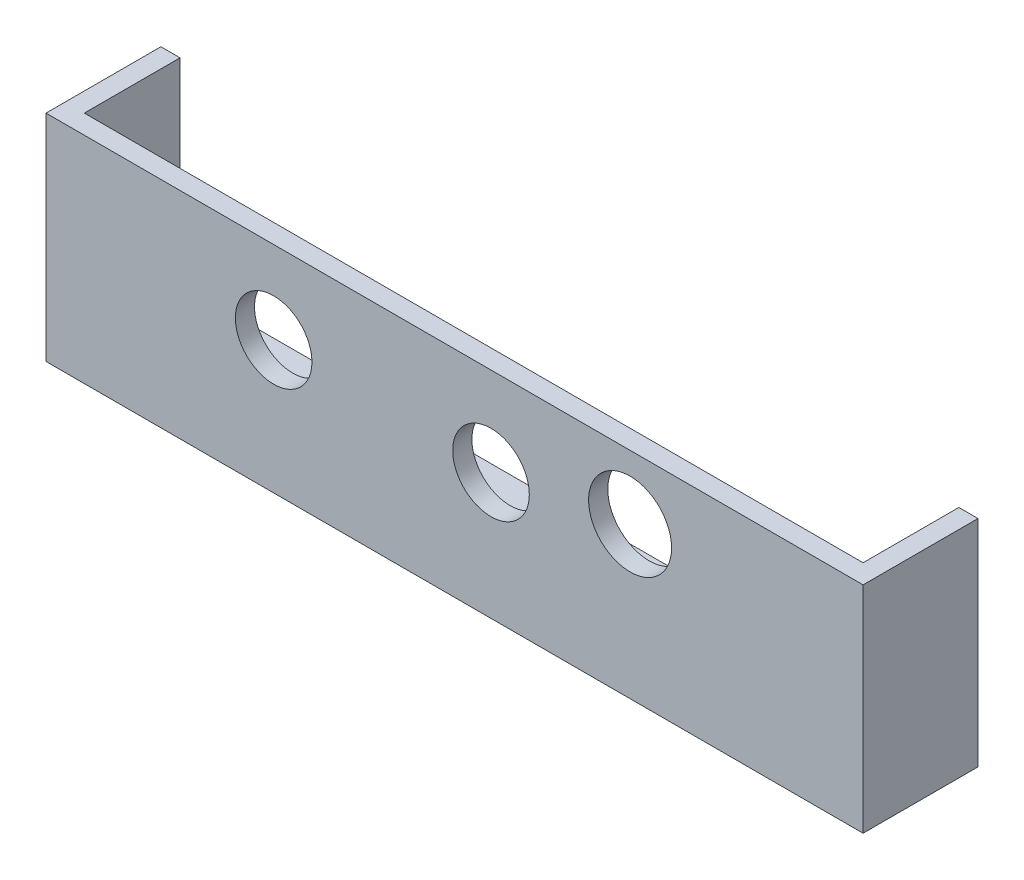
SolidWorks part; units mm, degrees
ref_plane "前基準面" through (0, 0, 0) normal (0, 0, 1) x (1, 0, 0)
ref_plane "上基準面" through (0, 0, 0) normal (0, 1, 0) x (1, 0, 0)
ref_plane "右基準面" through (0, 0, 0) normal (1, 0, 0) x (0, 0, -1)
sketch "草圖1" plane through (0, 0, 0) normal (0, 0, 1) x (1, 0, 0)
  line L1 (-94.9808, -38.4301) -> (33.0192, -38.4301)
  line L2 (-94.9808, -38.4301) -> (-94.9808, -72.1301)
  line L3 (-94.9808, -72.1301) -> (33.0192, -72.1301)
  line L4 (33.0192, -38.4301) -> (33.0192, -72.1301)
  line L5 (-84.9808, -38.4301) -> (23.0192, -38.4301) construction
  line L6 (-84.9808, -68.6301) -> (23.0192, -68.6301) construction
  line L7 (29.0192, -38.4301) -> (29.0192, -68.6301) construction
  line L8 (-90.9808, -38.4301) -> (-90.9808, -68.6301) construction
  circle A0 centre (-3.4808, -48.4301) radius 6.5
  circle A1 centre (-25.2697, -52.3301) radius 6
  circle A2 centre (-59.3197, -51.3801) radius 6
  dimension "D3" = 13
  dimension "D4" = 12
  dimension "D5" = 12
  dimension "D1" = 128
  dimension "D2" = 33.7
  dimension "D6" = 0
  dimension "D7" = 3.5
  dimension "D8" = 4
  dimension "D9" = 4
extrude "填料-伸長1" add sketch "草圖1" along normal blind 3
sketch "草圖2" plane through (0, 0, 0) normal (0, 0, -1) x (-1, 0, 0)
  line L9 (91.9808, -38.4301) -> (91.9808, -69.1301)
  line L10 (91.9808, -69.1301) -> (-30.0192, -69.1301)
  line L11 (-30.0192, -69.1301) -> (-30.0192, -38.4301)
  line L12 (91.9808, -38.4301) -> (91.9808, -69.1301)
  line L13 (91.9808, -69.1301) -> (-30.0192, -69.1301)
  line L14 (-30.0192, -69.1301) -> (-30.0192, -38.4301)
  line L15 (-33.0192, -38.4301) -> (-30.0192, -38.4301)
  line L16 (91.9808, -38.4301) -> (94.9808, -38.4301)
  line L18 (94.9808, -38.4301) -> (94.9808, -72.1301)
  line L19 (94.9808, -72.1301) -> (-33.0192, -72.1301)
  line L20 (-33.0192, -72.1301) -> (-33.0192, -38.4301)
  line L21 (94.9808, -38.4301) -> (94.9808, -72.1301)
  line L22 (94.9808, -72.1301) -> (-33.0192, -72.1301)
  line L23 (-33.0192, -72.1301) -> (-33.0192, -38.4301)
  dimension "D1" = 3
  dimension "D2" = 0
extrude "填料-伸長2" add sketch "草圖2" along normal blind 15
